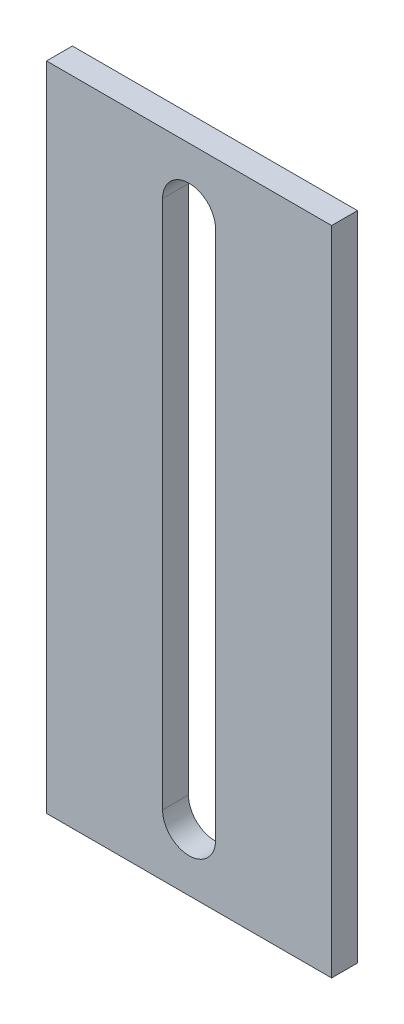
SolidWorks part; units mm, degrees
ref_plane "Alzado" through (0, 0, 0) normal (0, 0, 1) x (1, 0, 0)
ref_plane "Planta" through (0, 0, 0) normal (0, 1, 0) x (1, 0, 0)
ref_plane "Vista lateral" through (0, 0, 0) normal (1, 0, 0) x (0, 0, -1)
sketch "Croquis1" plane through (0, 0, 0) normal (0, 0, 1) x (1, 0, 0)
  line L0 (0, -65) -> (0, 65) construction
  line L1 (35, -80) -> (-35, -80)
  line L2 (35, -80) -> (35, 80)
  line L3 (35, 80) -> (-35, 80)
  line L4 (-35, -80) -> (-35, 80)
  line L5 (35, -80) -> (-35, 80) construction
  line L6 (35, 80) -> (-35, -80) construction
  line L7 (-6.5, -65) -> (-6.5, 65)
  line L8 (6.5, -65) -> (6.5, 65)
  arc A0 (-6.5, -65) -> (6.5, -65) centre (0, -65) ccw
  arc A1 (6.5, 65) -> (-6.5, 65) centre (0, 65) ccw
  point P0 (0, 0)
  point P8 (0, 0)
  dimension "D3" = 6.5
  dimension "D1" = 70
  dimension "D2" = 160
  dimension "D4" = 130
extrude "Saliente-Extruir1" add sketch "Croquis1" along normal blind 6.35
